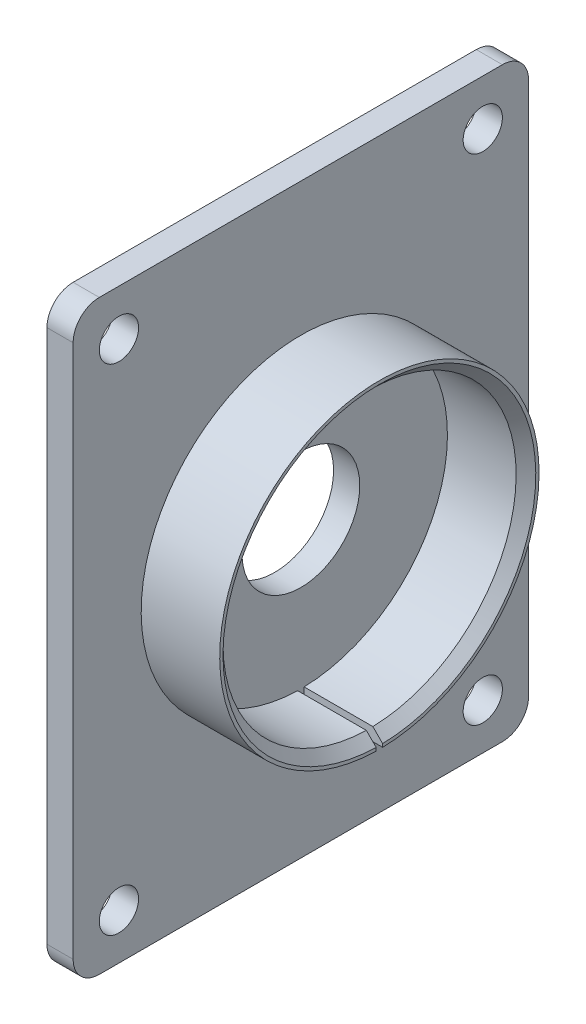
SolidWorks part; units mm, degrees
ref_plane "Front Plane" through (0, 0, 0) normal (1, 0, 0) x (0, 1, 0)
ref_plane "Top Plane" through (0, 0, 0) normal (0, 0, 1) x (0, 1, 0)
ref_plane "Right Plane" through (0, 0, 0) normal (0, 1, 0) x (-1, 0, 0)
sketch "Sketch1" plane through (0, 0, 0) normal (1, 0, 0) x (0, 1, 0)
  line L0 (-12.2, 0) -> (-11.2, 0) construction
  line L1 (-12.1974, -0.25) -> (-11.1972, -0.25)
  line L2 (-12.1974, 0.25) -> (-11.1972, 0.25)
  arc A0 (-11.1972, -0.25) -> (-11.1972, 0.25) centre (0, 0) ccw
  arc A1 (-12.1974, -0.25) -> (-12.1974, 0.25) centre (0, 0) ccw
  dimension "D1" = 22.4
  dimension "D2" = 24.4
  dimension "D3" = 0.5
extrude "Boss-Extrude1" add sketch "Sketch1" along normal blind 6
sketch "Sketch4" plane through (0, 0, 0) normal (-1, 0, 0) x (0, -1, 0)
  line L0 (0, 0) -> (0, 42.7171) construction
  line L1 (0, 0) -> (-46.5379, 0) construction
  line L2 (22.4, -17.4) -> (22.4, 17.4)
  line L4 (-22.4, -17.4) -> (-22.4, 17.4)
  line L5 (-22.4, 17.4) -> (22.4, 17.4)
  line L7 (-22.4, -17.4) -> (22.4, 17.4) construction
  line L8 (-22.4, 17.4) -> (22.4, -17.4) construction
  line L9 (-22.4, -17.4) -> (22.4, -17.4)
  circle A0 centre (-18.9, 13.9) radius 1.5
  circle A1 centre (18.9, 13.9) radius 1.5
  circle A2 centre (-18.9, -13.9) radius 1.5
  circle A3 centre (18.9, -13.9) radius 1.5
  point P13 (-22.4, 0)
  point P14 (0, 17.4)
  point P15 (22.4, 0)
  dimension "D1" = 3
  dimension "D2" = 37.8
  dimension "D3" = 27.8
  dimension "D4" = 2
  dimension "D5" = 2
extrude "Boss-Extrude3" add sketch "Sketch4" along normal blind 2
fillet "Fillet1" radius 2 4 edges at (-1, -22.4, 17.4) (-1, -22.4, -17.4) (-1, 22.4, -17.4) (-1, 22.4, 17.4)
chamfer "Chamfer1" distance 0.75 angle 45 1 edges at (6, 11.2, 0)
sketch "Sketch5" plane through (0, 0, 0) normal (1, 0, 0) x (0, 1, 0)
  circle A0 centre (0, 0) radius 4.5
  dimension "D1" = 9
extrude "Cut-Extrude1" cut sketch "Sketch5" against normal through all
